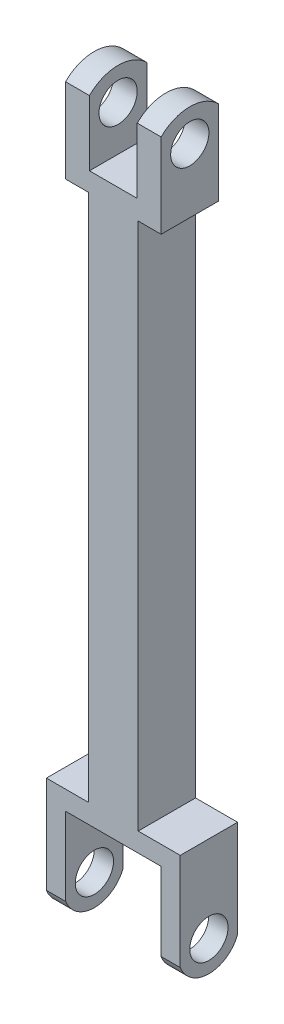
SolidWorks part; units mm, degrees
ref_plane "Alzado" through (0, 0, 0) normal (0, 0, 1) x (1, 0, 0)
ref_plane "Planta" through (0, 0, 0) normal (0, 1, 0) x (1, 0, 0)
ref_plane "Vista lateral" through (0, 0, 0) normal (1, 0, 0) x (0, 0, -1)
sketch "Croquis1" plane through (0, 0, 0) normal (0, 0, 1) x (1, 0, 0)
  line L1 (-11.0078, 72.4285) -> (-6.0078, 72.4285)
  line L2 (-6.0078, 72.4285) -> (-6.0078, 39.4285)
  line L3 (-6.0078, 39.4285) -> (-11.0078, 39.4285)
  line L5 (-11.0078, 72.4285) -> (-11.0078, 39.4285)
  dimension "D1" = 5
  dimension "D2" = 33
extrude "Saliente-Extruir1" add sketch "Croquis1" along normal blind 3
sketch "Croquis3" plane through (0, 39.4285, 0) normal (0, -1, 0) x (1, 0, 0)
  line L0 (-12.0078, 3) -> (-5.0078, 3)
  line L1 (-5.0078, 3) -> (-5.0078, 0)
  line L2 (-5.0078, 0) -> (-12.0078, 0)
  line L3 (-12.0078, 0) -> (-12.0078, 3)
  line L4 (-11.0078, 3) -> (-6.0078, 3) construction
  point P7 (-8.5078, 3)
  point P8 (-8.5078, 3)
  dimension "D1" = 7
extrude "Saliente-Extruir2" add sketch "Croquis3" along normal blind 7
sketch "Croquis4" plane through (0, 0, 3) normal (0, 0, 1) x (1, 0, 0)
  line L0 (-10.9978, 32.4285) -> (-10.9978, 38.4285)
  line L1 (-5.0078, 32.4285) -> (-12.0078, 32.4285) construction
  line L2 (-10.9978, 38.4285) -> (-6.0178, 38.4285)
  line L3 (-6.0178, 38.4285) -> (-6.0178, 32.4285)
  line L4 (-6.0178, 32.4285) -> (-10.9978, 32.4285)
  point P4 (-8.5078, 32.4285)
  point P7 (-8.5078, 32.4285)
  dimension "D1" = 4.98
  dimension "D2" = 6
extrude "Cortar-Extruir1" cut sketch "Croquis4" against normal up to next
sketch "Croquis5" plane through (-12.0078, 0, 0) normal (-1, 0, 0) x (0, 0, 1)
  line L0 (3, 72.4285) -> (0, 72.4285) construction
  line L1 (3, 39.4285) -> (0, 39.4285) construction
  circle A0 centre (1.5, 70.4144) radius 1
  circle A1 centre (1.5, 34.9179) radius 1
  point P7 (1.5, 72.4285)
  point P10 (1.5, 39.4285)
  dimension "D1" = 2
  dimension "D2" = 2
extrude "Cortar-Extruir4" cut sketch "Croquis5" against normal blind 15
sketch "Croquis7" plane through (-12.0078, 0, 0) normal (-1, 0, 0) x (0, 0, 1)
  line L2 (3, 71.4709) -> (3, 72.8216)
  line L3 (3, 72.8216) -> (0, 72.8216)
  line L4 (0, 72.8216) -> (0, 71.4709)
  line L5 (0, 34.344) -> (0, 31.9616)
  line L6 (0, 31.9616) -> (3, 31.9616)
  line L7 (3, 31.9616) -> (3, 34.344)
  arc A0 (3, 71.4709) -> (0, 71.4709) centre (1.5, 69.9669) ccw
  arc A1 (0, 34.344) -> (3, 34.344) centre (1.5, 34.9179) ccw
extrude "Cortar-Extruir5" cut sketch "Croquis7" against normal blind 15
sketch "Croquis8" plane through (0, 0, 3) normal (0, 0, 1) x (1, 0, 0)
  line L0 (-9.7578, 68.0613) -> (-9.7578, 72.3877)
  line L1 (-9.7578, 72.3877) -> (-7.2578, 72.3877)
  line L2 (-7.2578, 72.3877) -> (-7.2578, 68.0613)
  line L3 (-7.2578, 68.0613) -> (-9.7578, 68.0613)
  line L4 (-6.0078, 71.4709) -> (-11.0078, 71.4709) construction
  point P6 (-8.5078, 71.4709)
  point P7 (-8.5078, 68.0613)
  dimension "D1" = 2.5
extrude "Cortar-Extruir6" cut sketch "Croquis8" against normal blind 10
sketch "Croquis9" plane through (0, 0, 3) normal (0, 0, 1) x (1, 0, 0)
  line L0 (-11.0078, 67.0613) -> (-9.8078, 67.0613)
  line L1 (-11.0078, 71.4709) -> (-11.0078, 39.4285) construction
  line L2 (-9.8078, 67.0613) -> (-9.8078, 39.4285)
  line L3 (-9.8078, 39.4285) -> (-11.0078, 39.4285)
  line L4 (-11.0078, 39.4285) -> (-11.0078, 67.0613)
  line L5 (-6.0078, 67.0613) -> (-7.2078, 67.0613)
  line L6 (-6.0078, 39.4285) -> (-6.0078, 71.4709) construction
  line L7 (-7.2078, 67.0613) -> (-7.2078, 39.4285)
  line L8 (-7.2078, 39.4285) -> (-6.0078, 39.4285)
  line L9 (-6.0078, 39.4285) -> (-6.0078, 67.0613)
  line L11 (-9.7578, 68.0613) -> (-7.2578, 68.0613) construction
  dimension "D1" = 1
  dimension "D2" = 1.2
  dimension "D3" = 1.2
extrude "Cortar-Extruir7" cut sketch "Croquis9" against normal up to next
